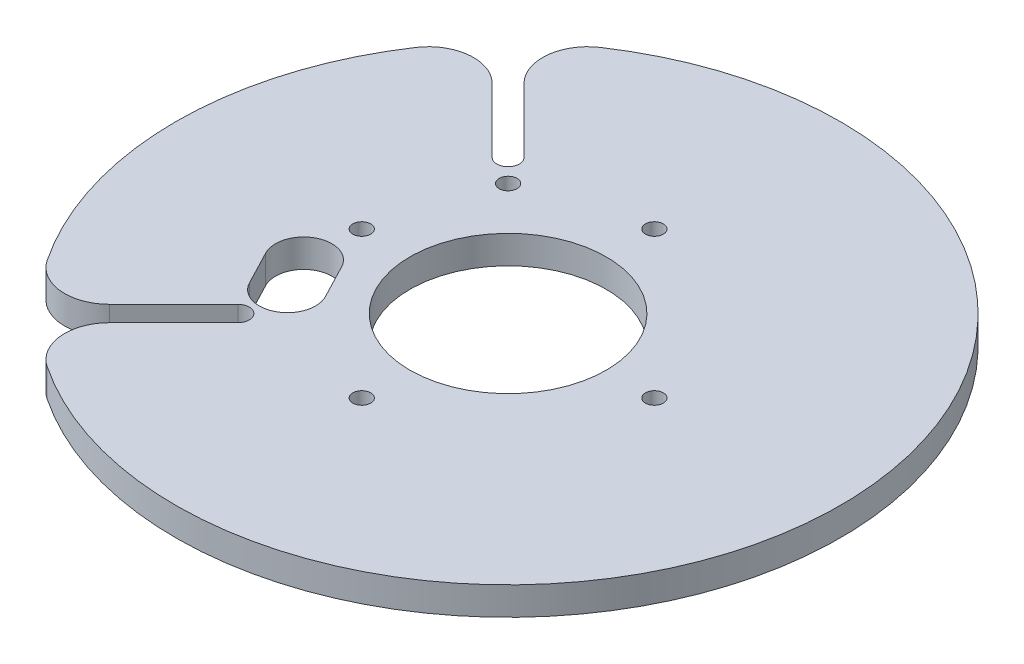
SolidWorks part; units mm, degrees
material "Acrylic (Medium-high impact)"
ref_plane "Front" through (0, 0, 0) normal (0, 0, 1) x (1, 0, 0)
ref_plane "Top" through (0, 0, 0) normal (0, 1, 0) x (1, 0, 0)
ref_plane "Right" through (0, 0, 0) normal (1, 0, 0) x (0, 0, -1)
sketch "Sketch1" plane through (0, 0, 0) normal (0, 1, 0) x (1, 0, 0)
  circle A0 centre (0, 0) radius 75
  dimension "D1" = 150
extrude "Boss-Extrude1" add sketch "Sketch1" along normal blind 6.35
sketch "Sketch45" plane through (0, 6.35, 0) normal (0, 1, 0) x (1, 0, 0)
  line L0 (-33.5359, -12.5897) -> (-29.5483, -20.2499) construction
  line L1 (-27.9034, -9.6576) -> (-23.9158, -17.3178)
  line L2 (-39.1685, -15.5218) -> (-35.1808, -23.182)
  line L3 (-30.48, -30.48) -> (-53.033, -53.033) construction
  line L4 (-28.6839, -32.2761) -> (-51.237, -54.8291)
  line L5 (-32.2761, -28.6839) -> (-54.8291, -51.237)
  line L6 (-30.48, 30.48) -> (-53.033, 53.033) construction
  line L7 (-32.2761, 28.6839) -> (-54.8291, 51.237)
  line L8 (-28.6839, 32.2761) -> (-51.237, 54.8291)
  line L9 (0, 0) -> (75, 0) construction
  line L10 (-33.5359, -12.5897) -> (0, 0) construction
  line L11 (0, 0) -> (-29.5483, -20.2499) construction
  line L12 (-31.5421, -16.4198) -> (0, 0) construction
  circle A0 centre (0, 0) radius 22.1615
  circle A1 centre (0, 0) radius 33.02 construction
  circle A2 centre (-25.4, 25.4) radius 2.0193
  circle A3 centre (0, 33.02) radius 2.0193
  circle A4 centre (33.02, 0) radius 2.0193
  circle A5 centre (0, -33.02) radius 2.0193
  circle A6 centre (-33.02, 0) radius 2.0193
  arc A7 (-27.9034, -9.6576) -> (-39.1685, -15.5218) centre (-33.5359, -12.5897) ccw
  arc A8 (-35.1808, -23.182) -> (-23.9158, -17.3178) centre (-29.5483, -20.2499) ccw
  arc A9 (-28.6839, -32.2761) -> (-32.2761, -28.6839) centre (-30.48, -30.48) ccw
  arc A10 (-54.8291, -51.237) -> (-51.237, -54.8291) centre (-53.033, -53.033) ccw
  arc A11 (-32.2761, 28.6839) -> (-28.6839, 32.2761) centre (-30.48, 30.48) ccw
  arc A12 (-51.237, 54.8291) -> (-54.8291, 51.237) centre (-53.033, 53.033) ccw
  circle A14 centre (0, 0) radius 75 construction
  point P16 (-31.5421, -16.4198)
  point P21 (-41.7565, -41.7565)
  point P28 (-41.7565, 41.7565)
  dimension "D1" = 44.323
  dimension "D5" = 4.0386
  dimension "D8" = 2.54
  dimension "D16" = 6.35
  dimension "D2" = 33.02
  dimension "D3" = 25.4
  dimension "D4" = 25.4
  dimension "D6" = 30.48
  dimension "D7" = 30.48
  dimension "D9" = 30.48
  dimension "D10" = 30.48
  dimension "D11" = 45
  dimension "D12" = 45
  dimension "D13" = 27.5
  dimension "D14" = 8.636
  dimension "D15" = 35.56
extrude "Cut-Extrude36" cut sketch "Sketch45" against normal through all
fillet "Fillet2" radius 10.16 4 edges at (-51.2065, 3.175, 54.7986) (-54.7986, 3.175, 51.2065) (-51.2065, 3.175, -54.7986) (-54.7986, 3.175, -51.2065)
